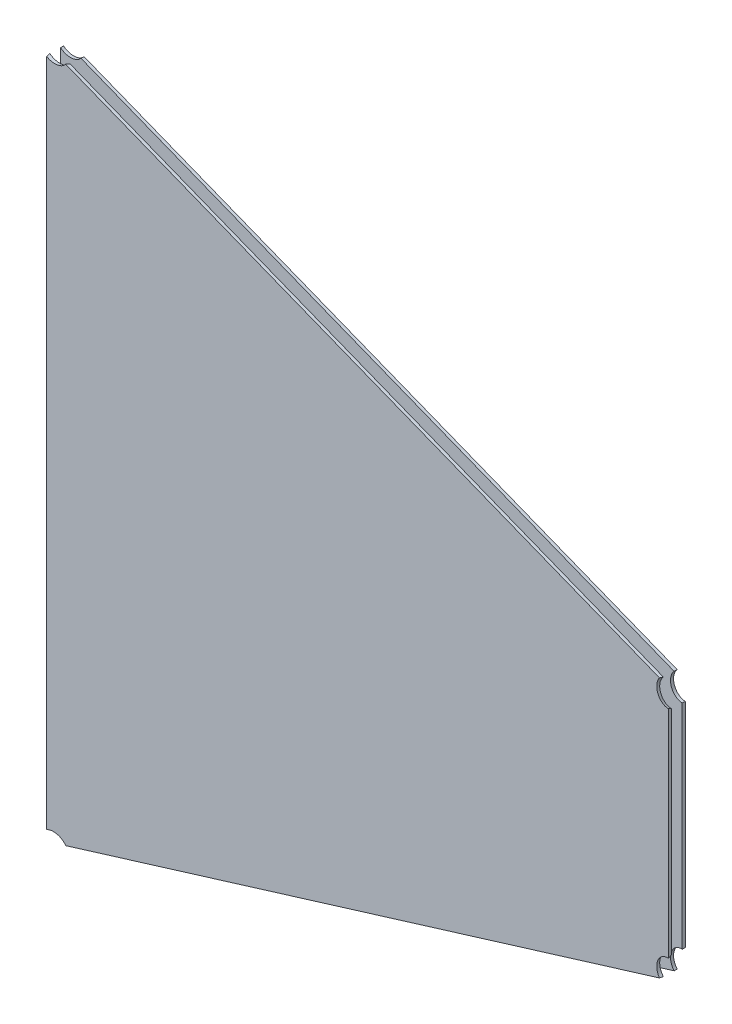
SolidWorks part; units mm, degrees
material "6061-T6 (SS)"
ref_plane "X-Y Datum" through (0, 0, 0) normal (0, 0, 1) x (1, 0, 0)
ref_plane "X-Z Datum" through (0, 0, 0) normal (0, 1, 0) x (1, 0, 0)
ref_plane "Y-Z Datum" through (0, 0, 0) normal (1, 0, 0) x (0, 0, -1)
ref_plane "Plane2" through (1.6076, 0, -38.1363) normal (-0.0421, 0, 0.9991) x (0.9991, 0, 0.0421)
sketch "Sketch1" plane through (1.6076, 0, -38.1363) normal (-0.0421, 0, 0.9991) x (0.9991, 0, 0.0421)
  line L4 (208.3305, 370.332) -> (905.5187, 136.1666)
  line L5 (905.5187, -136.1666) -> (905.5187, 136.1666)
  line L6 (208.3305, -370.332) -> (905.5187, -136.1666)
  line L7 (208.3305, -370.332) -> (208.3305, 370.332)
extrude "Boss-Extrude1" add sketch "Sketch1" along normal mid plane 3.175
ref_plane "Plane3" through (906.3228, 181.6751, 111.4979) normal (0, 0.4229, 0.9062) x (1, 0, 0)
sketch "Sketch2" plane through (906.3228, 181.6751, 111.4979) normal (0, 0.4229, 0.9062) x (1, 0, 0)
  circle A0 centre (0, 0) radius 13.081
  dimension "D1" = 26.162
extrude "Cut-Extrude1" cut sketch "Sketch2" against normal through all
mirror "Mirror1" about plane through (0, 0, 0) normal (0, 1, 0) of "Cut-Extrude1"
ref_plane "Plane4" through (18.074, 370.332, 262.2731) normal (0.5681, 0, -0.823) x (-0.823, 0, -0.5681)
sketch "Sketch3" plane through (18.074, 370.332, 262.2731) normal (0.5681, 0, -0.823) x (-0.823, 0, -0.5681)
  circle A0 centre (0, 0) radius 13.081
  dimension "D1" = 26.162
extrude "Cut-Extrude2" cut sketch "Sketch3" against normal through all and the other way through all
mirror "Mirror2" about plane through (0, 0, 0) normal (0, 1, 0) of "Cut-Extrude2"
ref_plane "Plane5" through (2.1424, 0, -50.8251) normal (-0.0421, 0, 0.9991) x (0.9991, 0, 0.0421)
sketch "Sketch4" plane through (2.1424, 0, -50.8251) normal (-0.0421, 0, 0.9991) x (0.9991, 0, 0.0421)
  line L4 (208.3305, 360.6376) -> (208.3305, -360.6376)
  line L5 (896.4507, 139.2123) -> (231.2181, 362.6447)
  line L6 (905.5187, -114.473) -> (905.5187, 114.473)
  line L7 (231.2181, -362.6447) -> (896.4507, -139.2123)
  line L8 (208.3305, 360.6376) -> (208.3305, -360.6376)
  line L9 (896.4507, 139.2123) -> (231.2181, 362.6447)
  line L10 (905.5187, -114.473) -> (905.5187, 114.473)
  line L11 (231.2181, -362.6447) -> (896.4507, -139.2123)
  ellipse E4 centre (218.7098, -370.332) end of major axis (203.2504, -370.332) minor radius 13.081 (231.2181, -362.6447) -> (208.3305, -360.6376) ccw
  ellipse E5 centre (218.7098, 370.332) end of major axis (203.2504, 370.332) minor radius 13.081 (208.3305, 360.6376) -> (231.2181, 362.6447) ccw
  ellipse E6 centre (905.4517, 128.9065) end of major axis (906.7505, 143.2958) minor radius 13.081 (896.4507, 139.2123) -> (905.5187, 114.473) ccw
  ellipse E7 centre (905.4517, -128.9065) end of major axis (906.7505, -143.2958) minor radius 13.081 (905.5187, -114.473) -> (896.4507, -139.2123) ccw
  ellipse E8 centre (218.7098, -370.332) end of major axis (203.2504, -370.332) minor radius 13.081 (231.2181, -362.6447) -> (208.3305, -360.6376) ccw
  ellipse E9 centre (218.7098, 370.332) end of major axis (203.2504, 370.332) minor radius 13.081 (208.3305, 360.6376) -> (231.2181, 362.6447) ccw
  ellipse E10 centre (905.4517, 128.9065) end of major axis (906.7505, 143.2958) minor radius 13.081 (896.4507, 139.2123) -> (905.5187, 114.473) ccw
  ellipse E11 centre (905.4517, -128.9065) end of major axis (906.7505, -143.2958) minor radius 13.081 (905.5187, -114.473) -> (896.4507, -139.2123) ccw
  dimension "D1" = 0
extrude "Boss-Extrude2" add sketch "Sketch4" against normal blind 3.175 separate body
